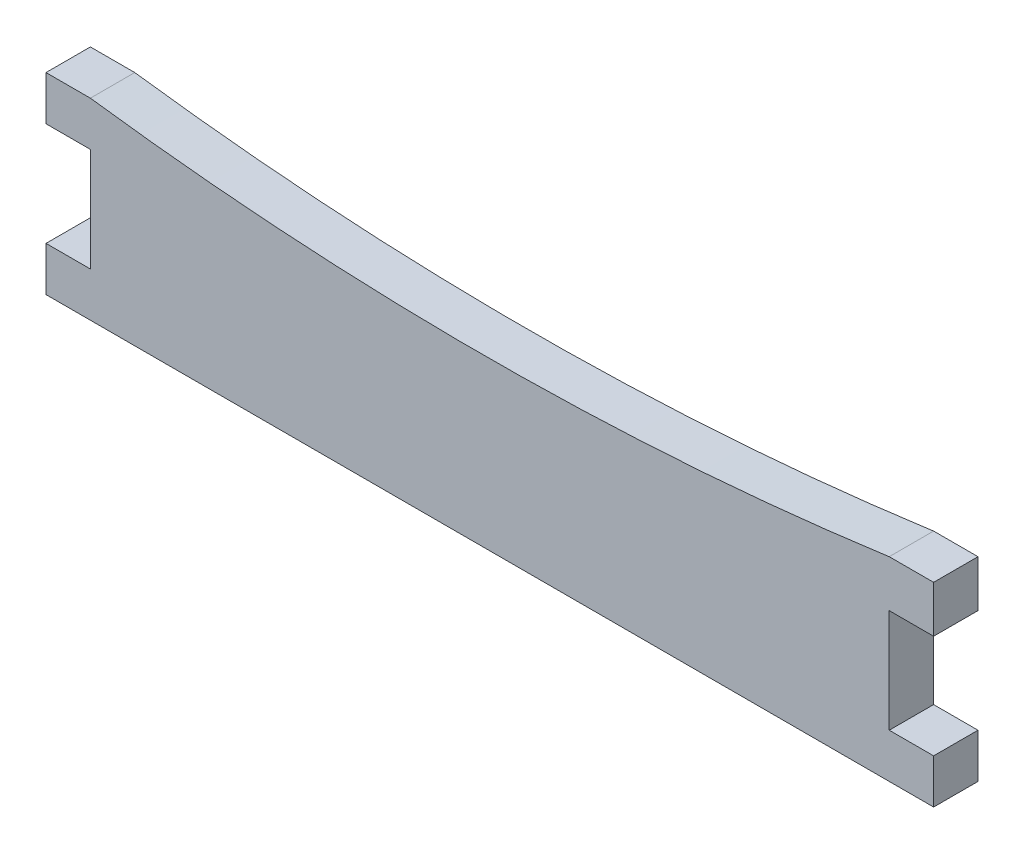
SolidWorks part; units mm, degrees
ref_plane "Front Plane" through (0, 0, 0) normal (0, 0, 1) x (1, 0, 0)
ref_plane "Top Plane" through (0, 0, 0) normal (0, 1, 0) x (1, 0, 0)
ref_plane "Right Plane" through (0, 0, 0) normal (1, 0, 0) x (0, 0, -1)
sketch "Sketch1" plane through (0, 0, 0) normal (0, 0, 1) x (1, 0, 0)
  line L0 (-38.1, 0) -> (38.1, 0)
  line L3 (38.1, 0) -> (38.1, 3.81)
  line L6 (38.1, 3.81) -> (34.29, 3.81)
  line L7 (34.29, 3.81) -> (34.29, 12.7)
  line L10 (34.29, 12.7) -> (38.1, 12.7)
  line L12 (38.1, 12.7) -> (38.1, 16.711)
  line L13 (38.1, 16.711) -> (34.29, 16.711)
  line L14 (-38.1, 0) -> (-38.1, 3.81)
  line L15 (-38.1, 3.81) -> (-34.29, 3.81)
  line L16 (-34.29, 3.81) -> (-34.29, 12.7)
  line L17 (-34.29, 12.7) -> (-38.1, 12.7)
  line L19 (-38.1, 12.7) -> (-38.1, 16.51)
  line L21 (-38.1, 16.51) -> (-34.29, 16.51)
  arc A1 (-34.29, 16.51) -> (34.29, 16.711) centre (-0.7378, 268.2842) ccw
  point P0 (0, 0)
  dimension "D3" = 254
  dimension "D1" = 3.81
  dimension "D2" = 3.81
  dimension "D4" = 3.81
  dimension "D7" = 3.81
  dimension "D8" = 12.7
  dimension "D9" = 68.58
extrude "Boss-Extrude1" add sketch "Sketch1" along normal blind 3.81
